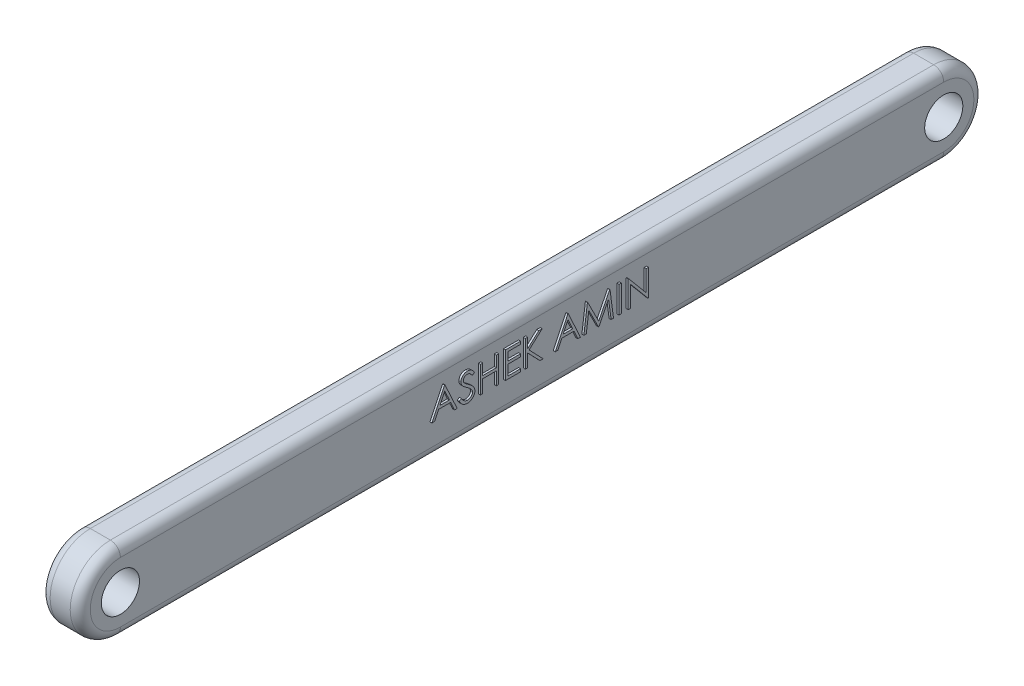
SolidWorks part; units mm, degrees
ref_plane "Front Plane" through (0, 0, 0) normal (0, 0, 1) x (1, 0, 0)
ref_plane "Top Plane" through (0, 0, 0) normal (0, 1, 0) x (1, 0, 0)
ref_plane "Right Plane" through (0, 0, 0) normal (1, 0, 0) x (0, 0, -1)
sketch "Sketch1" plane through (0, 0, 0) normal (1, 0, 0) x (0, 0, -1)
  line L0 (-20.5, 0) -> (20.5, 0) construction
  line L1 (-20.5, 2) -> (20.5, 2)
  line L2 (-20.5, -2) -> (20.5, -2)
  arc A0 (-20.5, 2) -> (-20.5, -2) centre (-20.5, 0) ccw
  arc A1 (20.5, -2) -> (20.5, 2) centre (20.5, 0) ccw
  circle A2 centre (20.5, 0) radius 0.95
  circle A3 centre (-20.5, 0) radius 0.95
  point P2 (0, 0)
  dimension "D1" = 41
  dimension "D2" = 1.9
  dimension "D3" = 1.9
  dimension "D4" = 2
extrude "Boss-Extrude1" add sketch "Sketch1" along normal mid plane 2
fillet "Fillet1" radius 0.5 8 edges at (-1, 0, -22.5) (-1, -2, 0) (-1, 0, 22.5) (1, 0, -22.5) (1, -2, 0) (1, 0, 22.5) (-1, 2, 0) (1, 2, 0)
move or copy body "Body-Move/Copy1" bodies to move or copy 101 copy no rotation origin (0, 0, 0) rotation axis (1, 0, 0) rotation angle 180
sketch "Sketch3" plane through (1, 0, 0) normal (1, 0, 0) x (0, 0, -1)
  text T0 "ASHEK AMIN" font "Century Gothic" height in points 5
extrude "Boss-Extrude3" add sketch "Sketch3" along normal blind 0.1
